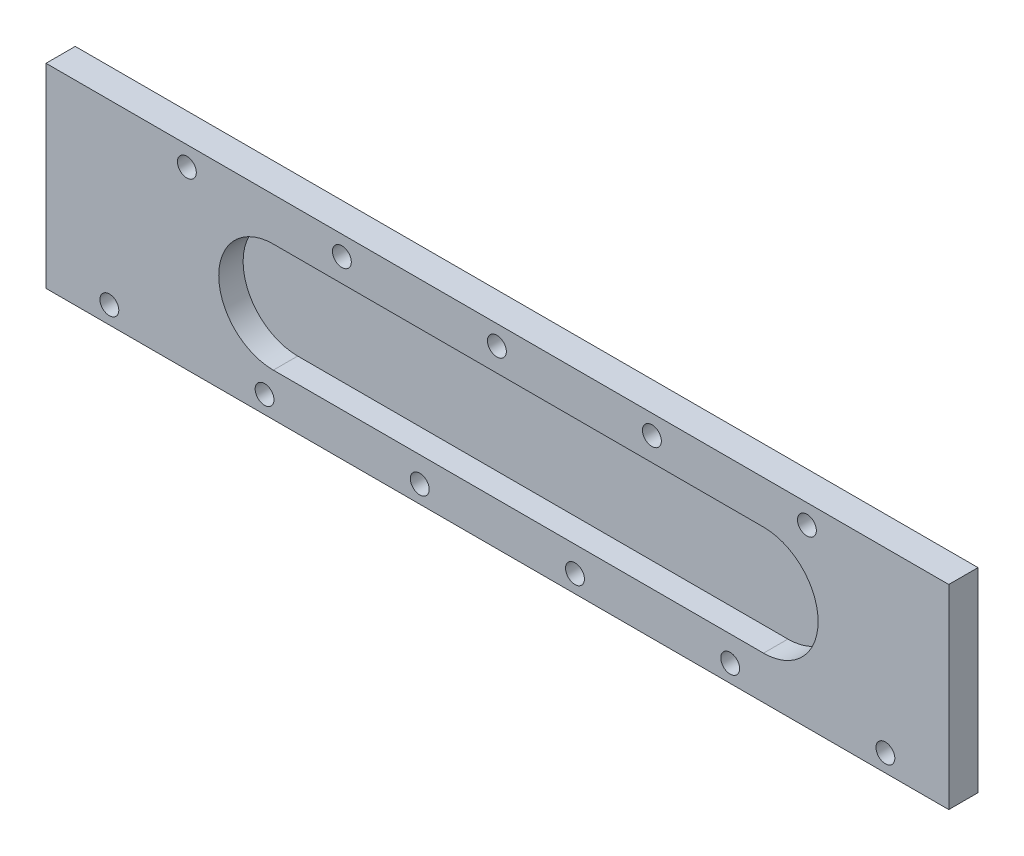
SolidWorks part; units mm, degrees
ref_plane "Front Plane" through (0, 0, 0) normal (0, 0, 1) x (1, 0, 0)
ref_plane "Top Plane" through (0, 0, 0) normal (0, 1, 0) x (1, 0, 0)
ref_plane "Right Plane" through (0, 0, 0) normal (1, 0, 0) x (0, 0, -1)
sketch "Sketch5" plane through (0, 0, 0) normal (0, 0, 1) x (1, 0, 0)
  line L1 (0, 0) -> (-235.204, 0)
  line L2 (0, 0) -> (0, 50.8)
  line L3 (0, 50.8) -> (-235.204, 50.8)
  line L4 (-235.204, 0) -> (-235.204, 50.8)
  dimension "D1" = 235.204
  dimension "D2" = 50.8
extrude "Boss-Extrude3" add sketch "Sketch5" along normal blind 7.62
sketch "Sketch6" plane through (0, 0, 7.62) normal (0, 0, 1) x (1, 0, 0)
  line L0 (0, 0) -> (0, 50.8) construction
  line L1 (0, 50.8) -> (-235.204, 50.8) construction
  line L3 (-48.26, 25.4) -> (-175.975, 25.4) construction
  line L7 (-48.26, 11.176) -> (-175.975, 11.176)
  line L8 (-48.26, 39.624) -> (-175.975, 39.624)
  arc A0 (-48.26, 11.176) -> (-48.26, 39.624) centre (-48.26, 25.4) ccw
  arc A1 (-175.975, 39.624) -> (-175.975, 11.176) centre (-175.975, 25.4) ccw
  point P14 (-112.1175, 25.4)
  dimension "D4" = 48.26
  dimension "D2" = 127.715
  dimension "D1" = 28.448
  dimension "D3" = 25.4
extrude "Cut-Extrude3" cut sketch "Sketch6" against normal blind 6.35
sketch "Sketch7" plane through (0, 0, 7.62) normal (0, 0, 1) x (1, 0, 0)
  line L0 (-235.204, 50.8) -> (-235.204, 0) construction
  line L1 (0, 0) -> (0, 50.8) construction
  line L2 (0, 50.8) -> (-235.204, 50.8) construction
  circle A0 centre (-218.694, 4.5485) radius 1.7923
  circle A1 centre (-178.2572, 4.5485) radius 1.7923
  circle A2 centre (-137.8204, 4.5485) radius 1.7923
  circle A3 centre (-97.3836, 4.5485) radius 1.7923
  circle A4 centre (-56.9468, 4.5485) radius 1.7923
  circle A5 centre (-16.51, 4.5485) radius 1.7923
  circle A6 centre (-198.501, 45.72) radius 3.5223
  circle A7 centre (-158.115, 45.72) radius 3.5223
  circle A8 centre (-117.729, 45.72) radius 3.5223
  circle A9 centre (-77.343, 45.72) radius 3.5223
  circle A10 centre (-36.957, 45.72) radius 2.697
  dimension "D2" = 16.51
  dimension "D4" = 40.4368
  dimension "D6" = 20.193
  dimension "D8" = 40.386
  dimension "D3" = 16.51
  dimension "D7" = 40.386
  dimension "D9" = 5.08
  dimension "D10" = 5.08
  dimension "D1" = 6
  dimension "D5" = 4
hole_wizard "#10 (0.1935) Diameter Hole1" positions "3DSketch1" profile "Sketch8" hole size "#10" standard "ANSI Inch" end condition through all
sketch3d "3DSketch1"
  point P0 (-198.501, 45.72, 7.62)
  point P3 (-158.115, 45.72, 7.62)
  point P6 (-117.729, 45.72, 7.62)
  point P9 (-77.343, 45.72, 7.62)
  point P12 (-36.957, 45.72, 7.62)
  point P15 (-218.694, 4.5485, 7.62)
  point P18 (-178.2572, 4.5485, 7.62)
  point P21 (-137.8204, 4.5485, 7.62)
  point P24 (-97.3836, 4.5485, 7.62)
  point P27 (-56.9468, 4.5485, 7.62)
  point P30 (-16.51, 4.5485, 7.62)
sketch "Sketch8" plane through (-198.501, 45.72, 7.62) normal (1, 0, 0) x (0, -1, 0)
  line L0 (0, 0) -> (0, 7.62)
  line L1 (0, 7.62) -> (2.4574, 7.62)
  line L2 (2.4574, 7.62) -> (2.4574, 0)
  line L5 (2.4574, 0) -> (0, 0)
  line L11 (0, -6.35) -> (0, 107.95) construction
  dimension "Thru Hole Dia." = 4.9149
  dimension "Thru Hole Depth" = 7.62
